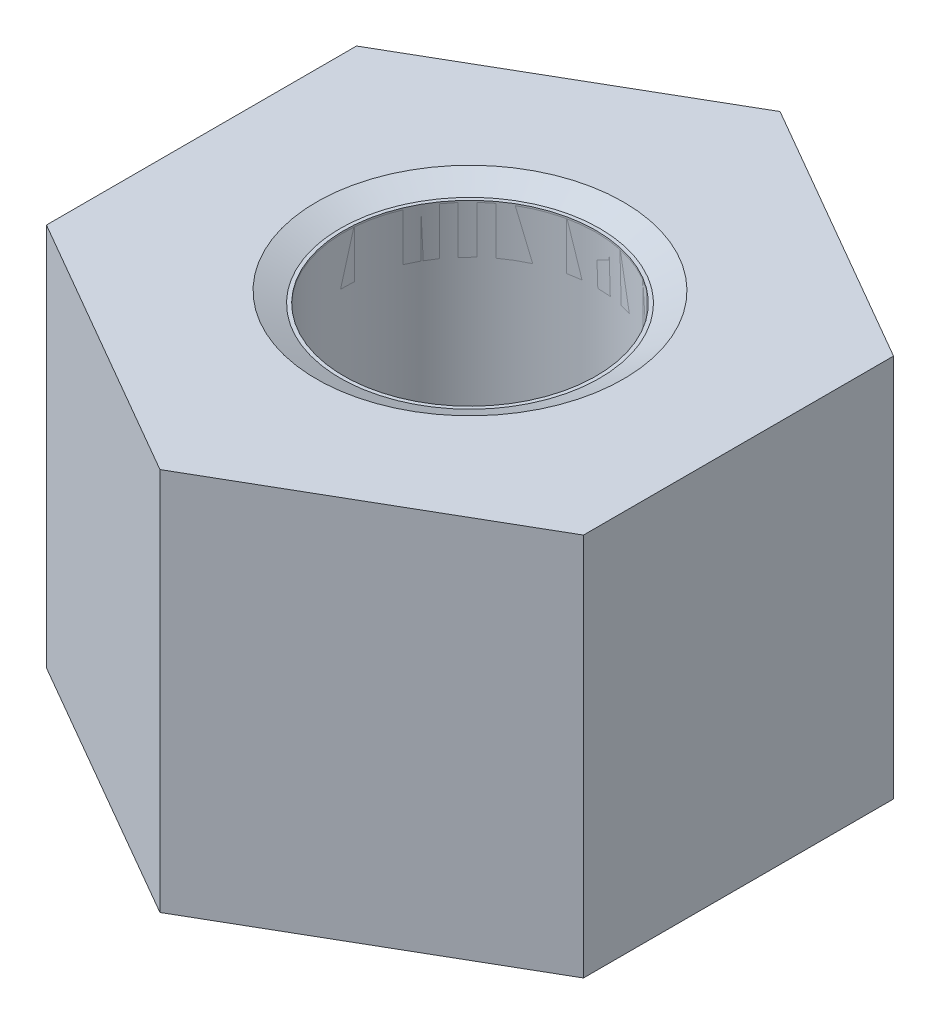
SolidWorks part; units mm, degrees
material "Alloy Steel"
ref_plane "Front" through (0, 0, 0) normal (0, 0, 1) x (1, 0, 0)
ref_plane "Top" through (0, 0, 0) normal (0, 1, 0) x (1, 0, 0)
ref_plane "Right" through (0, 0, 0) normal (1, 0, 0) x (0, 0, -1)
sketch "Sketch1" plane through (0, 0, 0) normal (0, 1, 0) x (1, 0, 0)
  line L1 (0, 6.4158) -> (-5.5563, 3.2079)
  line L2 (-5.5563, 3.2079) -> (-5.5563, -3.2079)
  line L3 (-5.5563, -3.2079) -> (0, -6.4158)
  line L4 (0, -6.4158) -> (5.5562, -3.2079)
  line L5 (5.5562, -3.2079) -> (5.5562, 3.2079)
  line L6 (5.5562, 3.2079) -> (0, 6.4158)
  circle A0 centre (0, 0) radius 5.5563 construction
  dimension "Hex Flats" = 11.1125
extrude "Extrude1" add sketch "Sketch1" along normal blind 7.9375
sketch "Sketch2" plane through (0, 0, 0) normal (1, 0, 0) x (0, 0, -1)
  line L0 (-3.175, 0) -> (-3.175, 7.9375) construction
  line L1 (0, 0) -> (3.175, 0)
  line L2 (0, 0) -> (0, 7.9375)
  line L3 (0, 7.9375) -> (3.175, 7.9375)
  line L4 (3.175, 0) -> (3.175, 7.9375)
  line L5 (-3.2079, 7.9375) -> (3.2079, 7.9375) construction
  line L7 (0, -3.175) -> (0, 0) construction
  dimension "Thread Dia" = 6.35
revolve "Revolve1" [suppressed] add sketch "Sketch2" angle 360 about L7
sketch "Sketch3" plane through (0, 0, 0) normal (1, 0, 0) x (0, 0, -1)
  line L0 (3.175, 7.9375) -> (-3.175, 7.9375) construction
  line L1 (-3.175, 7.9375) -> (-3.175, 6.6675) construction
  line L2 (-3.175, 6.6675) -> (3.175, 7.9375) construction
  line L3 (3.175, 7.9375) -> (3.2061, 7.7818) construction
  line L4 (3.2061, 7.7818) -> (3.4241, 6.6922)
  line L5 (3.4241, 6.6922) -> (2.6722, 6.9465)
  line L6 (2.6722, 6.9465) -> (2.6099, 7.2579)
  line L7 (2.6099, 7.2579) -> (3.2061, 7.7818)
  line L8 (2.641, 7.1022) -> (3.3151, 7.237) construction
  line L9 (3.175, 7.9375) -> (3.175, 7.209) construction
  line L10 (3.175, 7.209) -> (-3.175, 5.939) construction
  line L11 (-3.175, 5.939) -> (-3.175, 6.6675) construction
  line L12 (-0.2727, 7.9375) -> (0.2727, 5.2105) construction
  line L13 (-3.175, 0) -> (-3.175, 7.9375) construction
  line L14 (0, 7.9375) -> (3.175, 7.9375) construction
  line L15 (3.175, 0) -> (3.175, 7.9375) construction
  point P13 (0, 6.574)
  dimension "D1" = 0.1588
  dimension "D2" = 0.3175
  dimension "Thread Pitch" = 1.27
  dimension "D4" = 60
  dimension "D5" = 1.27
revolve "Cut-Revolve1" [suppressed] cut sketch "Sketch3" angle 360 about L12
pattern_linear "LPattern1" [suppressed] count 6 spacing 1.27 along (0, 1, 0) count 2 spacing 1.27 along (0, 1, 0)
sketch "Sketch4" plane through (0, 0, 0) normal (1, 0, 0) x (0, 0, -1)
  line L0 (0, 7.9375) -> (3.175, 7.9375)
  line L1 (3.175, 7.9375) -> (2.6099, 7.674)
  line L2 (2.6099, 7.674) -> (2.6099, 0.2635)
  line L3 (2.6099, 0.2635) -> (3.175, 0)
  line L4 (3.175, 0) -> (0, 0)
  line L5 (0, 0) -> (0, 7.9375)
  line L6 (3.175, 0) -> (3.175, 7.9375) construction
  line L7 (0, 7.9375) -> (3.175, 7.9375) construction
  line L8 (0, 0) -> (3.175, 0) construction
  line L9 (0, 0) -> (0, 7.9375) construction
  line L10 (0, 7.9375) -> (0, 8.561) construction
  dimension "D1" = 25
revolve "Cut-Revolve2" cut sketch "Sketch4" angle 360 about L10
combine bodies "Combine1" [suppressed] operation type subtract main body 112 bodies to subtract 111
sketch "Sketch5" plane through (0, 0, 0) normal (1, 0, 0) x (0, 0, -1)
  line L0 (0, 0) -> (5.5563, 0)
  line L1 (5.5563, 0) -> (6.4158, 0.4008)
  line L2 (6.4158, 0.4008) -> (6.4158, 6.2138)
  line L3 (6.4158, 6.2138) -> (5.5562, 6.6146)
  line L4 (4.2333, 7.9375) -> (4.2333, 9.2075)
  line L5 (4.2333, 9.2075) -> (7.6858, 9.2075)
  line L6 (7.6858, 9.2075) -> (7.6858, -1.27)
  line L7 (7.6858, -1.27) -> (0, -1.27)
  line L8 (0, -1.27) -> (0, 0)
  line L9 (5.5562, 6.6146) -> (5.5563, 0) construction
  line L10 (0, 0) -> (3.175, 0) construction
  line L13 (6.4158, 3.3073) -> (7.6858, 3.3073) construction
  line L14 (6.4158, 7.9375) -> (6.4158, 0) construction
  line L15 (0, 0) -> (0, 9.2075) construction
  line L20 (0, 9.2075) -> (4.2333, 9.2075) construction
  line L22 (0, 7.9375) -> (3.175, 7.9375) construction
  arc A0 (5.5562, 6.6146) -> (4.2333, 7.9375) centre (4.2333, 6.6146) ccw
  dimension "D1" = 25
  dimension "D2" = 1.27
  dimension "D3" = 7.9375
  dimension "D4" = 1.3229
revolve "Cut-Revolve3" [suppressed] cut sketch "Sketch5" angle 360 about L15
sketch "Sketch6" plane through (0, 0, 0) normal (1, 0, 0) x (0, 0, -1)
  line L0 (0, 6.6146) -> (5.4038, 6.6146)
  line L1 (4.2333, 7.7851) -> (3.4216, 7.7851)
  line L2 (0, 9.2075) -> (0, 6.6146)
  line L3 (3.4216, 9.2075) -> (0, 9.2075)
  line L4 (0, 9.2075) -> (4.2333, 9.2075) construction
  line L5 (0, 0) -> (0, 9.2075) construction
  line L6 (0, 9.2075) -> (0, 44.323) construction
  line L7 (3.4216, 7.7851) -> (3.4216, 9.2075)
  line L8 (4.2333, 7.9375) -> (4.2333, 7.7851) construction
  line L9 (3.4216, 7.7851) -> (2.6099, 7.7851) construction
  line L10 (2.6099, 7.7851) -> (2.6099, 7.674) construction
  arc A0 (5.4038, 6.6146) -> (4.2333, 7.7851) centre (4.2333, 6.6146) ccw
  arc A1 (5.5562, 6.6146) -> (4.2333, 7.9375) centre (4.2333, 6.6146) ccw construction
  dimension "D1" = 0.1524
revolve "Cut-Revolve4" [suppressed] cut sketch "Sketch6" angle 360 about L6
sketch "Sketch7" plane through (0, 0, 0) normal (1, 0, 0) x (0, 0, -1)
  line L0 (2.6099, 6.6908) -> (5.325, 6.6908)
  line L1 (4.2333, 7.7089) -> (2.6099, 7.7089)
  line L2 (2.6099, 7.7089) -> (2.6099, 6.6908)
  line L3 (2.6099, 6.6908) -> (0, 6.6908) construction
  line L4 (0, 6.6908) -> (0, 7.7089) construction
  line L5 (0, 7.7089) -> (2.6099, 7.7089) construction
  line L6 (2.6099, 6.6908) -> (2.6099, 6.6146) construction
  line L7 (0, 6.6146) -> (5.4038, 6.6146) construction
  line L8 (4.2333, 7.7089) -> (4.2333, 7.7851) construction
  arc A0 (5.325, 6.6908) -> (4.2333, 7.7089) centre (4.2333, 6.6146) ccw
  arc A2 (5.4038, 6.6146) -> (4.2333, 7.7851) centre (4.2333, 6.6146) ccw construction
  dimension "D1" = 0.0762
revolve "Revolve2" add sketch "Sketch7" angle 360 about L4
equation "\"D1@Sketch3\"=\"Thread Pitch@Sketch3\"/8"
equation "\"D2@Sketch3\"=\"Thread Pitch@Sketch3\"/4"
equation "\"D5@Sketch3\"=\"Thread Pitch@Sketch3\""
equation "\"D4@LPattern1\"=\"Thread Pitch@Sketch3\""
equation "\"D3@LPattern1\"=\"Thread Pitch@Sketch3\""
equation "\"D1@LPattern1\"=\"Height@Extrude1\"/\"Thread Pitch@Sketch3\""
equation "\"D4@Sketch5\"=\"Height@Extrude1\"/6"
